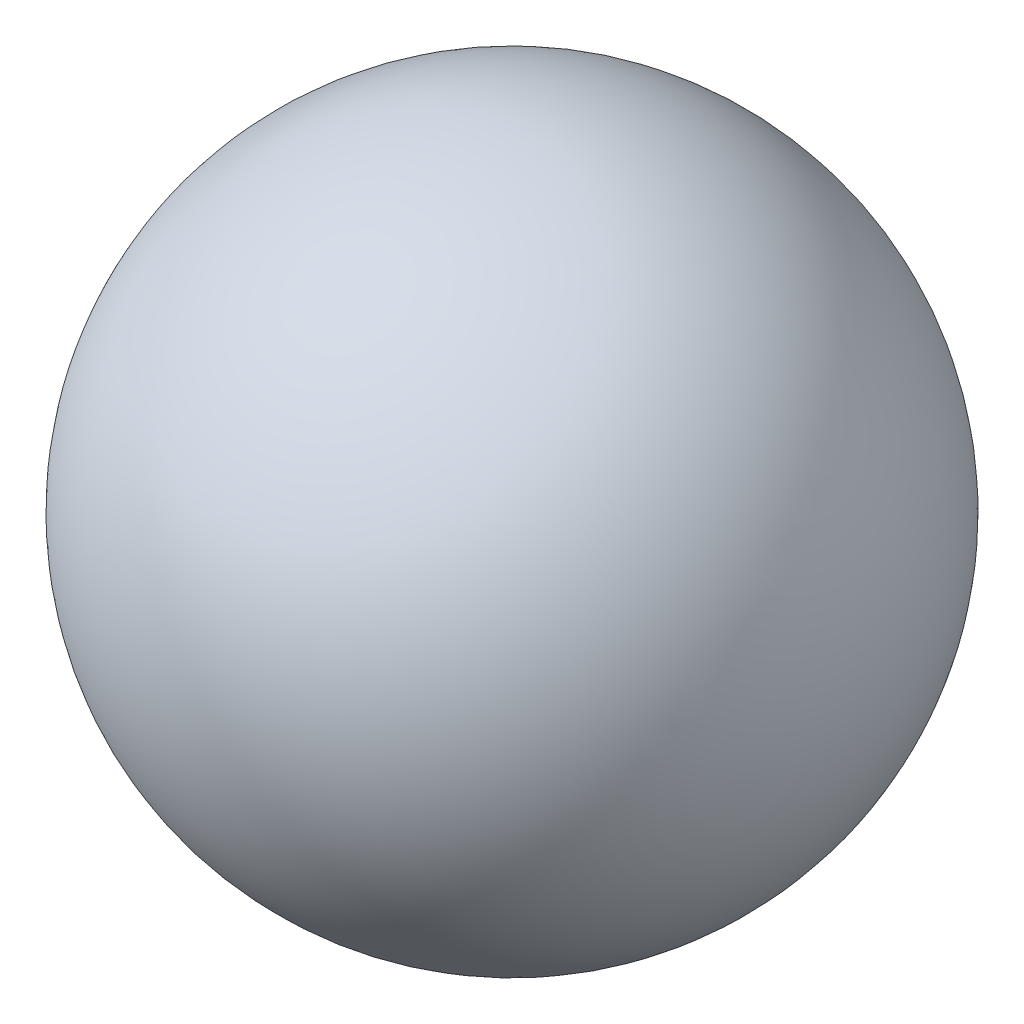
SolidWorks part; units mm, degrees
ref_plane "前视基准面" through (0, 0, 0) normal (0, 0, 1) x (1, 0, 0)
ref_plane "上视基准面" through (0, 0, 0) normal (0, 1, 0) x (1, 0, 0)
ref_plane "右视基准面" through (0, 0, 0) normal (1, 0, 0) x (0, 0, -1)
other "Configuration Table"
sketch "草图1" plane through (0, 0, 0) normal (0, 1, 0) x (1, 0, 0)
  line L0 (0, 0) -> (299.161, 0) construction
  line L1 (-120, 0) -> (120, 0)
  arc A0 (120, 0) -> (-120, 0) centre (0, 0) ccw
revolve "旋转5" add sketch "草图1" angle 360 about L0
